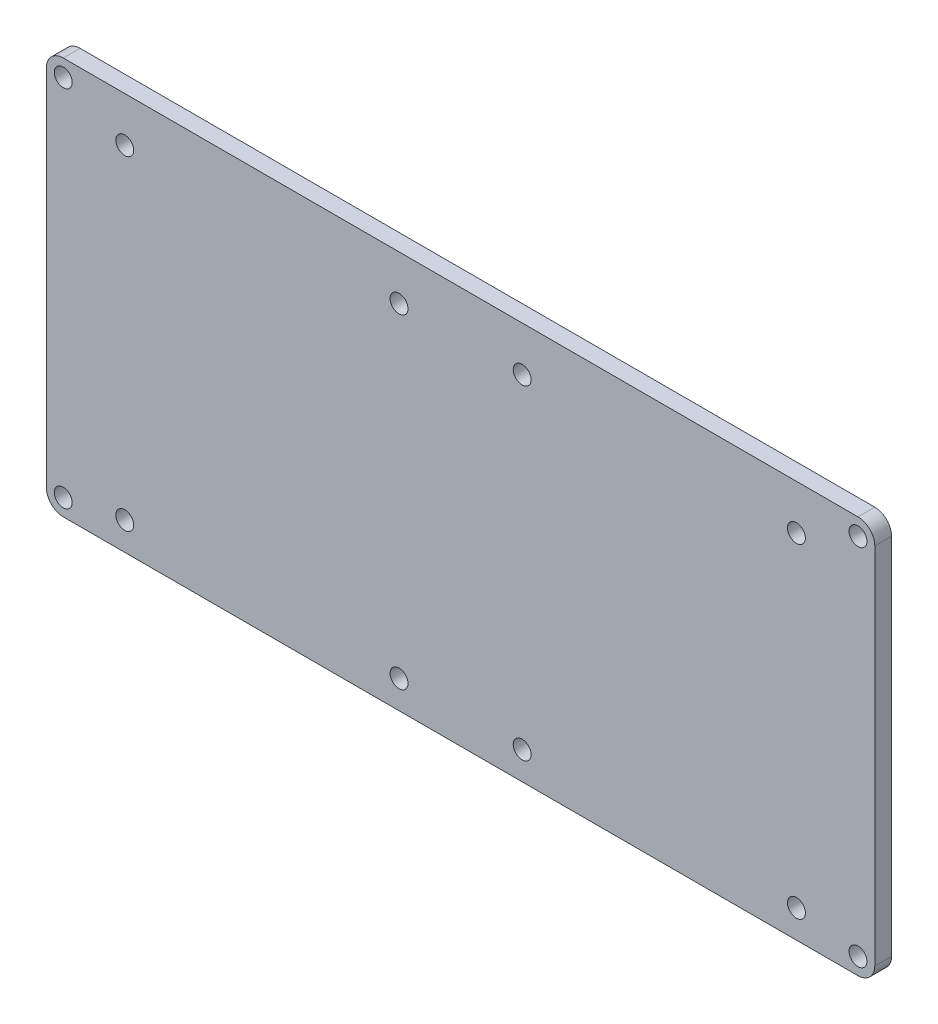
SolidWorks part; units mm, degrees
ref_plane "前视基准面" through (0, 0, 0) normal (0, 0, 1) x (1, 0, 0)
ref_plane "上视基准面" through (0, 0, 0) normal (0, 1, 0) x (1, 0, 0)
ref_plane "右视基准面" through (0, 0, 0) normal (1, 0, 0) x (0, 0, -1)
sketch "草图1" plane through (0, 0, 0) normal (0, 0, 1) x (1, 0, 0)
  line L0 (74, 71) -> (74, 0) construction
  line L1 (3, 0) -> (145, 0)
  line L2 (0, 3) -> (0, 68)
  line L3 (3, 71) -> (145, 71)
  line L4 (148, 3) -> (148, 68)
  arc A0 (0, 3) -> (3, 0) centre (3, 3) ccw
  arc A1 (145, 0) -> (148, 3) centre (145, 3) ccw
  arc A2 (148, 68) -> (145, 71) centre (145, 68) ccw
  arc A3 (3, 71) -> (0, 68) centre (3, 68) ccw
  circle A4 centre (3, 3) radius 1.6
  circle A5 centre (145, 3) radius 1.6
  circle A6 centre (145, 68) radius 1.6
  circle A7 centre (3, 68) radius 1.6
  circle A8 centre (14, 63) radius 1.6
  circle A9 centre (63, 63) radius 1.6
  circle A10 centre (63, 5) radius 1.6
  circle A11 centre (14, 5) radius 1.6
  circle A12 centre (85, 63) radius 1.6
  circle A13 centre (85, 5) radius 1.6
  circle A14 centre (134, 5) radius 1.6
  circle A15 centre (134, 63) radius 1.6
  point P7 (0, 0)
  point P39 (0, 0)
  dimension "D1" = 3
  dimension "D2" = 2
  dimension "D3" = 2
  dimension "D4" = 2
  dimension "D5" = 2
extrude "凸台-拉伸1" add sketch "草图1" along normal blind 3
